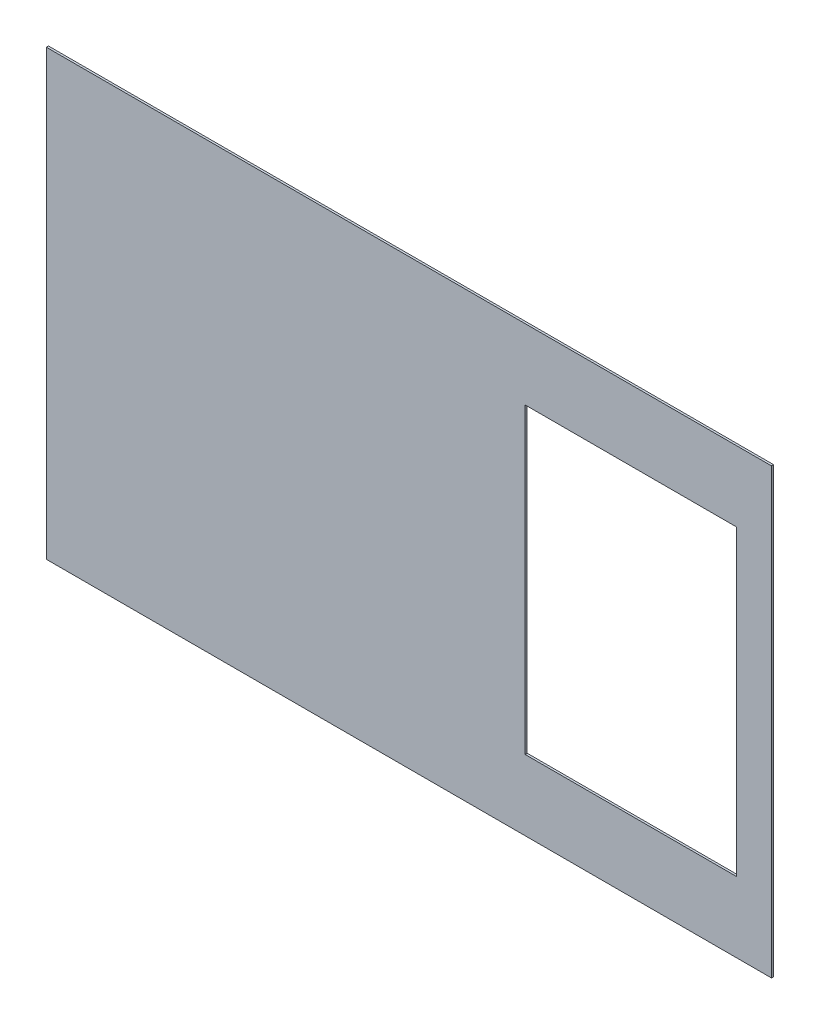
SolidWorks part; units mm, degrees
ref_plane "Plan de face" through (0, 0, 0) normal (0, 0, 1) x (1, 0, 0)
ref_plane "Plan de dessus" through (0, 0, 0) normal (0, 1, 0) x (1, 0, 0)
ref_plane "Plan de droite" through (0, 0, 0) normal (1, 0, 0) x (0, 0, -1)
sketch "Esquisse1" plane through (0, 0, 0) normal (0, 0, 1) x (1, 0, 0)
  line L1 (-515, -315) -> (515, -315)
  line L2 (-515, -315) -> (-515, 315)
  line L3 (-515, 315) -> (515, 315)
  line L4 (515, -315) -> (515, 315)
  line L5 (-515, -315) -> (515, 315) construction
  line L6 (-515, 315) -> (515, -315) construction
  point P0 (0, 0)
  dimension "D1" = 1030
  dimension "D2" = 630
extrude "Boss.-Extru.1" add sketch "Esquisse1" along normal blind 3
sketch "Esquisse2" plane through (0, 0, 0) normal (0, 0, -1) x (-1, 0, 0)
  line L6 (0, 0) -> (0, 308.6321) construction
  line L7 (-165, -215) -> (-465, -215)
  line L8 (-465, 215) -> (-465, -215)
  line L9 (-165, 215) -> (-465, 215)
  line L10 (-165, 215) -> (-165, -215)
  dimension "D1" = 300
  dimension "D2" = 430
extrude "Enlèv. mat.-Extru.1" cut sketch "Esquisse2" against normal blind 10
